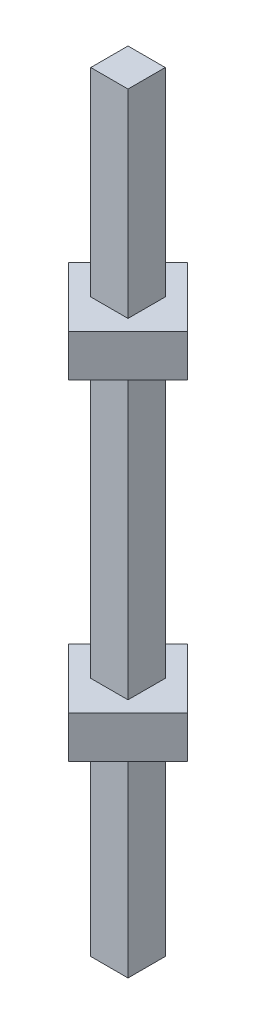
SolidWorks part; units mm, degrees
ref_plane "前视基准面" through (0, 0, 0) normal (0, 0, 1) x (1, 0, 0)
ref_plane "上视基准面" through (0, 0, 0) normal (0, 1, 0) x (1, 0, 0)
ref_plane "右视基准面" through (0, 0, 0) normal (1, 0, 0) x (0, 0, -1)
sketch "草图1" plane through (0, 0, 0) normal (0, 1, 0) x (1, 0, 0)
  line L0 (0, 0) -> (15, 0)
  line L1 (15, 0) -> (15, 15)
  line L2 (15, 15) -> (0, 15)
  line L3 (0, 15) -> (0, 0)
  dimension "D1" = 15
  dimension "D2" = 15
extrude "凸台-拉伸1" add sketch "草图1" along normal blind 310
ref_plane "基准面1" through (0, 230, 0) normal (0, 1, 0) x (1, 0, 0)
ref_plane "基准面2" through (0, 80, 0) normal (0, -1, 0) x (-1, 0, 0)
sketch "草图3" plane through (0, 80, 0) normal (0, -1, 0) x (-1, 0, 0)
  line L0 (12.6076, 7.5) -> (-28.0546, 7.5) construction
  line L2 (-7.5, 22.135) -> (-7.5, -7.9231) construction
  line L3 (-7.5, 31.5416) -> (-31.5416, 7.5)
  line L4 (-31.5416, 7.5) -> (-7.5, -16.5416)
  line L5 (-7.5, -16.5416) -> (16.5416, 7.5)
  line L6 (16.5416, 7.5) -> (-7.5, 31.5416)
  point P6 (13.568, -18.6139)
  point P9 (-7.5, 24.3993)
  dimension "D1" = 34
  dimension "D2" = 34
  dimension "D3" = 34
  dimension "D4" = 34
extrude "凸台-拉伸3" add sketch "草图3" against normal blind 17
sketch "草图4" plane through (0, 230, 0) normal (0, 1, 0) x (1, 0, 0)
  line L4 (7.5, 31.5416) -> (-16.5416, 7.5)
  line L5 (-16.5416, 7.5) -> (7.5, -16.5416)
  line L6 (7.5, -16.5416) -> (31.5416, 7.5)
  line L7 (31.5416, 7.5) -> (7.5, 31.5416)
  line L8 (7.5, 31.5416) -> (-16.5416, 7.5)
  line L9 (-16.5416, 7.5) -> (7.5, -16.5416)
  line L10 (7.5, -16.5416) -> (31.5416, 7.5)
  line L11 (31.5416, 7.5) -> (7.5, 31.5416)
  dimension "D1" = 0
extrude "凸台-拉伸4" add sketch "草图4" against normal blind 17
